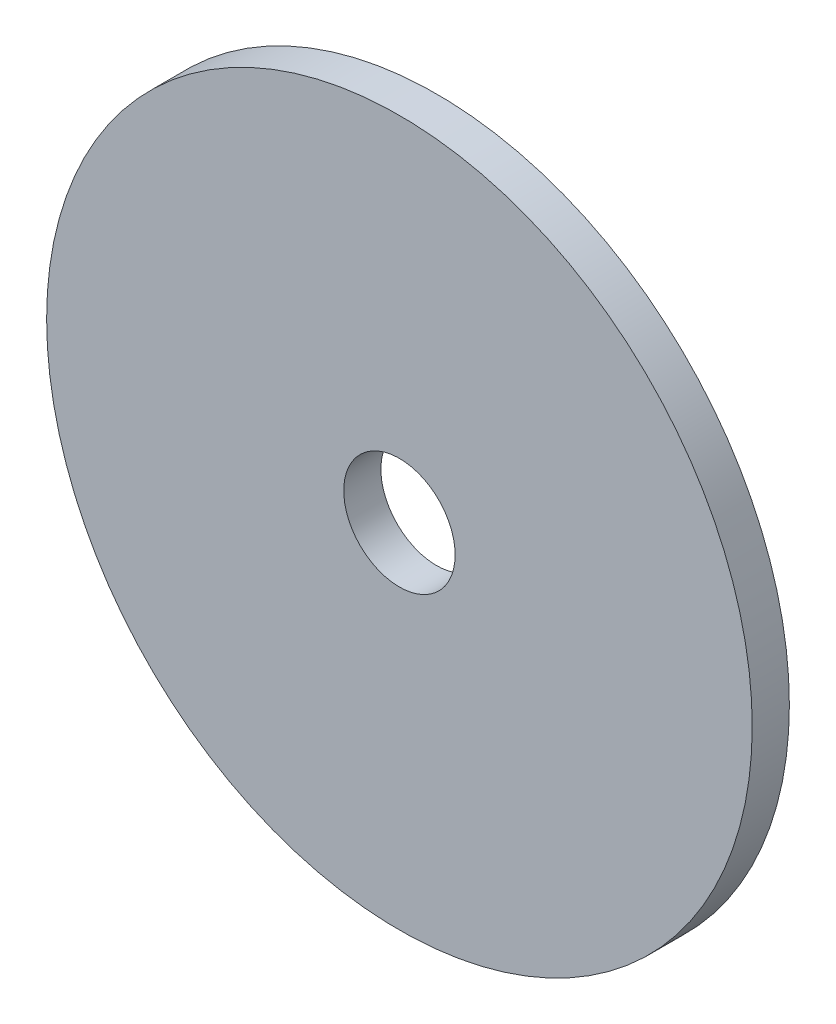
SolidWorks part; units mm, degrees
ref_plane "Alzado" through (0, 0, 0) normal (0, 0, 1) x (1, 0, 0)
ref_plane "Planta" through (0, 0, 0) normal (0, 1, 0) x (1, 0, 0)
ref_plane "Vista lateral" through (0, 0, 0) normal (1, 0, 0) x (0, 0, -1)
sketch "Croquis1" plane through (0, 0, 0) normal (0, 0, 1) x (1, 0, 0)
  circle A0 centre (0, 0) radius 9.5
extrude "Saliente-Extruir1" add sketch "Croquis1" along normal blind 1
sketch "Croquis2" plane through (0, 0, 1) normal (0, 0, 1) x (1, 0, 0)
  circle A0 centre (0, 0) radius 1.5
extrude "Cortar-Extruir1" cut sketch "Croquis2" against normal blind 1
